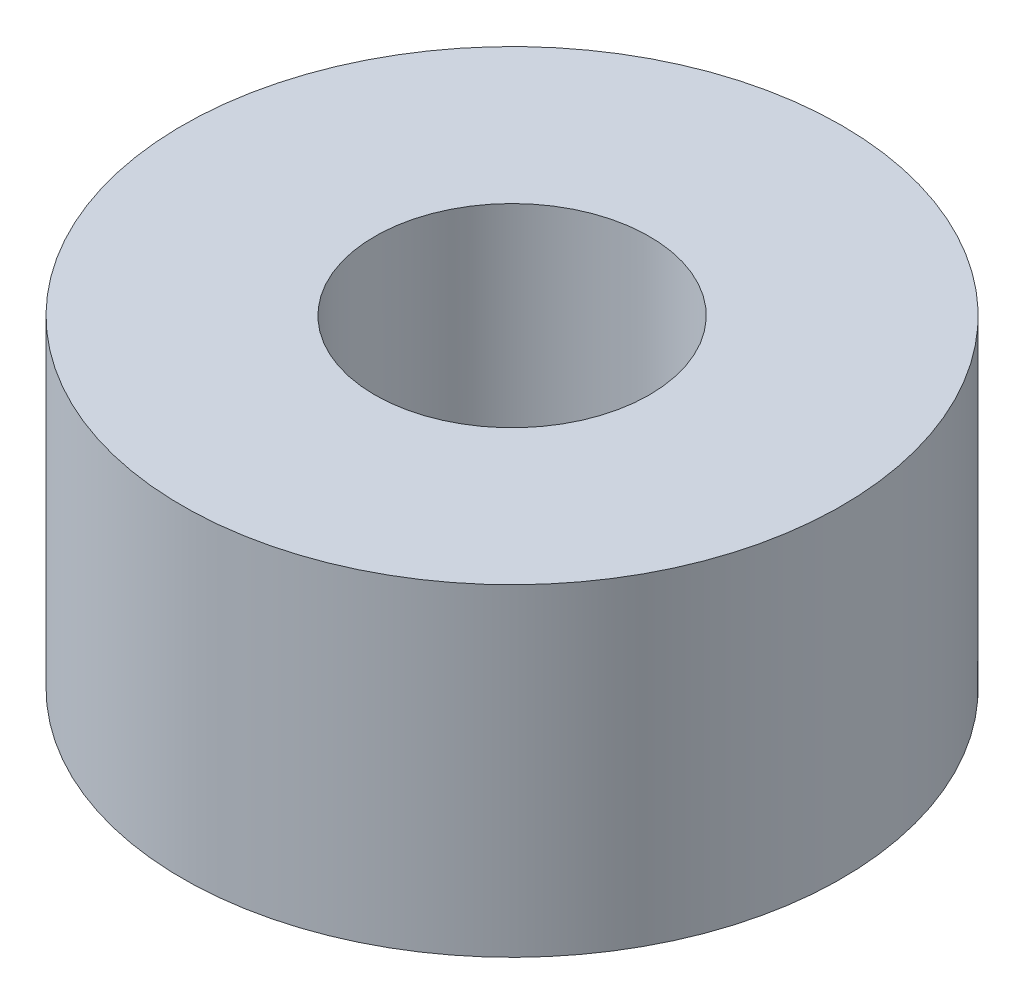
SolidWorks part; units mm, degrees
ref_plane "前视基准面" through (0, 0, 0) normal (0, 0, 1) x (1, 0, 0)
ref_plane "上视基准面" through (0, 0, 0) normal (0, 1, 0) x (1, 0, 0)
ref_plane "右视基准面" through (0, 0, 0) normal (1, 0, 0) x (0, 0, -1)
sketch "草图1" plane through (0, 0, 0) normal (0, 0, 1) x (1, 0, 0)
  line L0 (0, 5.2) -> (4.8, 5.2)
  line L1 (4.8, 5.2) -> (4.8, 0.5)
  line L2 (2.8, 0) -> (0, 0)
  line L3 (2.8, 0) -> (4.8, 0.5)
  line L4 (0, 0) -> (0, 5.3855) construction
  line L5 (0, 0) -> (0, 5.2)
  line L6 (4.8, 0.5) -> (3.5442, 0.5) construction
  dimension "D1" = 5.2
  dimension "D3" = 2
  dimension "D4" = 4.8
revolve "旋转1" add sketch "草图1" angle 360 about L4
sketch "草图2" plane through (0, 0, 0) normal (0, -1, 0) x (1, 0, 0)
  circle A0 centre (0, 0) radius 2
  dimension "D1" = 4
extrude "切除-拉伸1" cut sketch "草图2" against normal blind 10
sketch "草图3" plane through (0, 0, 0) normal (0, -1, 0) x (1, 0, 0)
  line L0 (2.2221, 0) -> (0, 0)
  line L1 (0, 0) -> (0, -2.2322)
